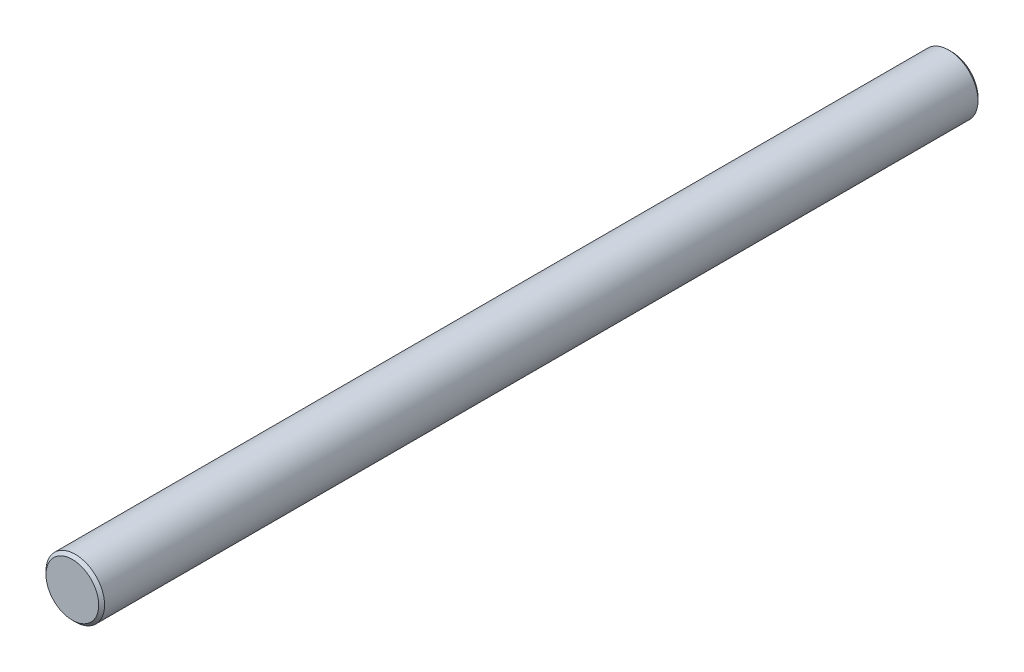
SolidWorks part; units mm, degrees
ref_plane "前视基准面" through (0, 0, 0) normal (0, 0, 1) x (1, 0, 0)
ref_plane "上视基准面" through (0, 0, 0) normal (0, 1, 0) x (1, 0, 0)
ref_plane "右视基准面" through (0, 0, 0) normal (1, 0, 0) x (0, 0, -1)
sketch "草图1" plane through (0, 0, 0) normal (0, 0, 1) x (1, 0, 0)
  circle A0 centre (0, 0) radius 2
extrude "凸台-拉伸1" add sketch "草图1" along normal blind 60
chamfer "倒角1" distance 0.2 angle 45 2 edges at (2, 0, 0) (2, 0, 60)
